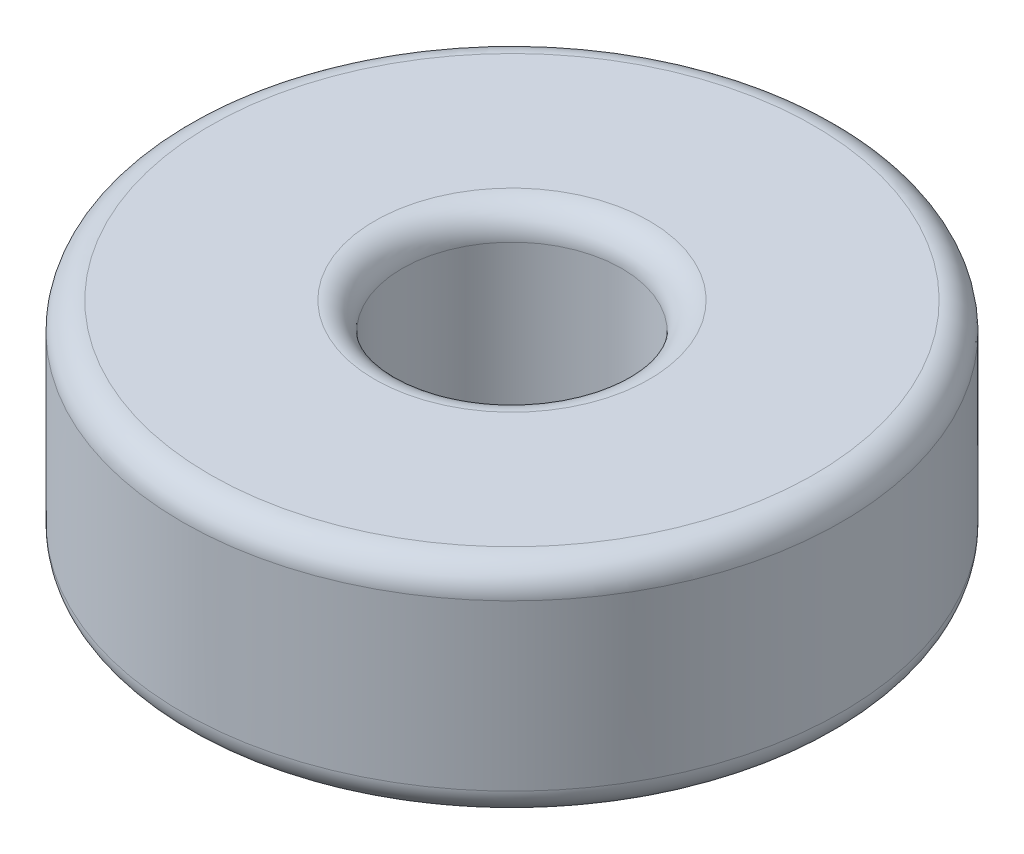
SolidWorks part; units mm, degrees
ref_plane "Plan de face" through (0, 0, 0) normal (0, 0, 1) x (1, 0, 0)
ref_plane "Plan de dessus" through (0, 0, 0) normal (0, 1, 0) x (1, 0, 0)
ref_plane "Plan de droite" through (0, 0, 0) normal (1, 0, 0) x (0, 0, -1)
sketch "Esquisse1" plane through (0, 0, 0) normal (0, 0, 1) x (1, 0, 0)
  line L0 (0, 0) -> (0, 4) construction
  line L1 (2, 0) -> (6, 0)
  line L2 (2, 0) -> (2, 4)
  line L3 (2, 4) -> (6, 4)
  line L4 (6, 0) -> (6, 4)
  dimension "D1" = 2
  dimension "D2" = 6
  dimension "D3" = 4
revolve "Révolution1" add sketch "Esquisse1" angle 360 about L0
fillet "Congé1" radius 0.5 4 edges at (0, 0, -2) (0, 0, -6) (0, 4, -6) (0, 4, -2)
